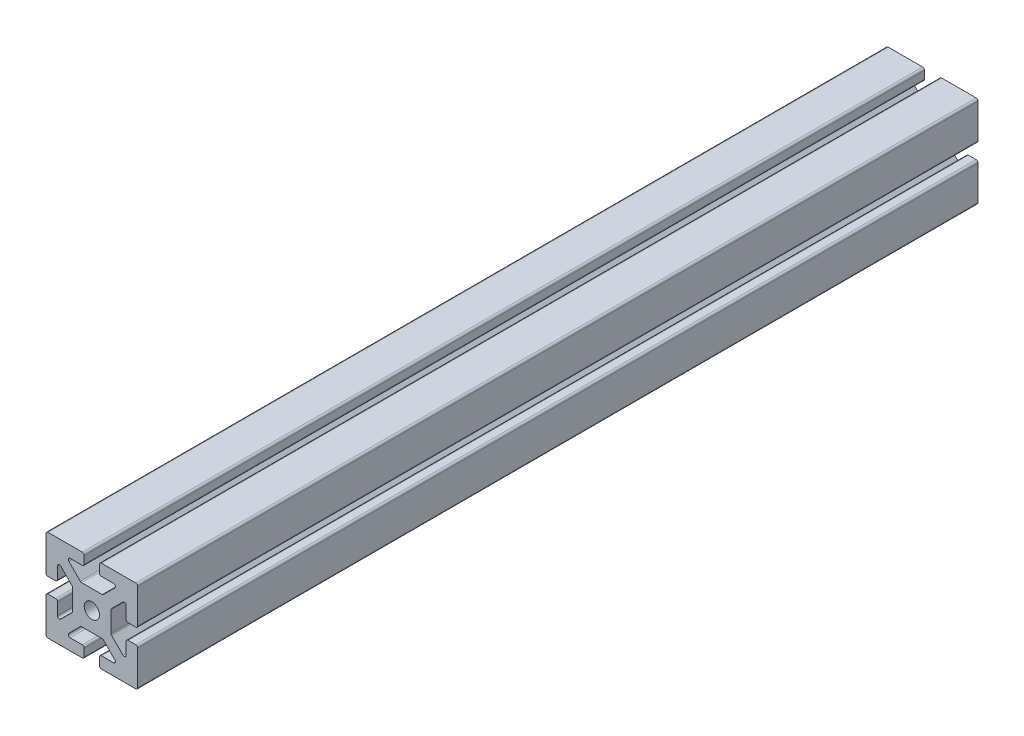
SolidWorks part; units mm, degrees
ref_plane "Front Plane" through (0, 0, 0) normal (0, 0, 1) x (1, 0, 0)
ref_plane "Top Plane" through (0, 0, 0) normal (0, 1, 0) x (1, 0, 0)
ref_plane "Right Plane" through (0, 0, 0) normal (1, 0, 0) x (0, 0, -1)
sketch "Sketch2" plane through (0, 0, 0) normal (0, 0, 1) x (1, 0, 0)
  line L0 (-707.1068, -707.1068) -> (34648.2323, 34648.2323) construction
  line L1 (-2.5, 0) -> (2.5, 0)
  line L2 (0, -2.5) -> (0, 2.5)
  line L3 (0, 2.5) -> (1.3358, 2.5)
  line L4 (2.5, -1.3358) -> (2.5, 1.3358)
  line L5 (1.4393, 2.5) -> (2.5, 1.4393)
  line L6 (1.5126, 2.5732) -> (3.0126, 4.0732)
  line L7 (2.8358, 4.5) -> (1.25, 4.5)
  line L8 (1, 4.75) -> (1, 5.75)
  line L9 (1.25, 6) -> (5.75, 6)
  line L10 (6, 5.75) -> (6, 1.25)
  line L11 (5.75, 1) -> (4.7486, 1)
  line L12 (4.4986, 1.25) -> (4.4986, 2.8344)
  line L13 (4.0718, 3.0111) -> (2.5732, 1.5126)
  line L14 (-707.1068, 707.1068) -> (34648.2323, -34648.2323) construction
  line L15 (4.0718, -3.0111) -> (2.5732, -1.5126)
  line L16 (4.4986, -1.25) -> (4.4986, -2.8344)
  line L17 (5.75, -1) -> (4.7486, -1)
  line L18 (6, -5.75) -> (6, -1.25)
  line L19 (1.25, -6) -> (5.75, -6)
  line L20 (1, -4.75) -> (1, -5.75)
  line L21 (2.8358, -4.5) -> (1.25, -4.5)
  line L22 (1.5126, -2.5732) -> (3.0126, -4.0732)
  line L23 (1.4393, -2.5) -> (2.5, -1.4393)
  line L24 (-1.3358, -2.5) -> (1.3358, -2.5)
  line L25 (707.1068, 707.1068) -> (-34648.2323, -34648.2323) construction
  line L26 (707.1068, -707.1068) -> (-34648.2323, 34648.2323) construction
  line L27 (-1.4393, -2.5) -> (-2.5, -1.4393)
  line L28 (-1.5126, -2.5732) -> (-3.0126, -4.0732)
  line L29 (-2.8358, -4.5) -> (-1.25, -4.5)
  line L30 (-1, -4.75) -> (-1, -5.75)
  line L31 (-1.25, -6) -> (-5.75, -6)
  line L32 (-6, -5.75) -> (-6, -1.25)
  line L33 (-5.75, -1) -> (-4.7486, -1)
  line L34 (-4.4986, -1.25) -> (-4.4986, -2.8344)
  line L35 (-4.0718, -3.0111) -> (-2.5732, -1.5126)
  line L36 (-4.0718, 3.0111) -> (-2.5732, 1.5126)
  line L37 (-4.4986, 1.25) -> (-4.4986, 2.8344)
  line L38 (-5.75, 1) -> (-4.7486, 1)
  line L39 (-6, 5.75) -> (-6, 1.25)
  line L40 (-1.25, 6) -> (-5.75, 6)
  line L41 (-1, 4.75) -> (-1, 5.75)
  line L42 (-2.8358, 4.5) -> (-1.25, 4.5)
  line L43 (-1.5126, 2.5732) -> (-3.0126, 4.0732)
  line L44 (-1.4393, 2.5) -> (-2.5, 1.4393)
  line L45 (-2.5, -1.3358) -> (-2.5, 1.3358)
  line L46 (0, 2.5) -> (-1.3358, 2.5)
  arc A0 (1.3358, 2.5) -> (1.5126, 2.5732) centre (1.3358, 2.75) ccw
  arc A1 (2.5, 1.3358) -> (2.5732, 1.5126) centre (2.75, 1.3358) cw
  arc A2 (3.0126, 4.0732) -> (2.8358, 4.5) centre (2.8358, 4.25) ccw
  arc A3 (4.4986, 2.8344) -> (4.0718, 3.0111) centre (4.2486, 2.8344) ccw
  arc A4 (4.7486, 1) -> (4.4986, 1.25) centre (4.7486, 1.25) cw
  arc A5 (6, 1.25) -> (5.75, 1) centre (5.75, 1.25) cw
  arc A6 (5.75, 6) -> (6, 5.75) centre (5.75, 5.75) cw
  arc A7 (1.25, 4.5) -> (1, 4.75) centre (1.25, 4.75) cw
  arc A8 (1, 5.75) -> (1.25, 6) centre (1.25, 5.75) cw
  arc A9 (1, -5.75) -> (1.25, -6) centre (1.25, -5.75) ccw
  arc A10 (1.25, -4.5) -> (1, -4.75) centre (1.25, -4.75) ccw
  arc A11 (5.75, -6) -> (6, -5.75) centre (5.75, -5.75) ccw
  arc A12 (6, -1.25) -> (5.75, -1) centre (5.75, -1.25) ccw
  arc A13 (4.7486, -1) -> (4.4986, -1.25) centre (4.7486, -1.25) ccw
  arc A14 (4.4986, -2.8344) -> (4.0718, -3.0111) centre (4.2486, -2.8344) cw
  arc A15 (3.0126, -4.0732) -> (2.8358, -4.5) centre (2.8358, -4.25) cw
  arc A16 (2.5, -1.3358) -> (2.5732, -1.5126) centre (2.75, -1.3358) ccw
  arc A17 (1.3358, -2.5) -> (1.5126, -2.5732) centre (1.3358, -2.75) cw
  arc A18 (-1.3358, -2.5) -> (-1.5126, -2.5732) centre (-1.3358, -2.75) ccw
  arc A19 (-2.5, -1.3358) -> (-2.5732, -1.5126) centre (-2.75, -1.3358) cw
  arc A20 (-3.0126, -4.0732) -> (-2.8358, -4.5) centre (-2.8358, -4.25) ccw
  arc A21 (-4.4986, -2.8344) -> (-4.0718, -3.0111) centre (-4.2486, -2.8344) ccw
  arc A22 (-4.7486, -1) -> (-4.4986, -1.25) centre (-4.7486, -1.25) cw
  arc A23 (-6, -1.25) -> (-5.75, -1) centre (-5.75, -1.25) cw
  arc A24 (-5.75, -6) -> (-6, -5.75) centre (-5.75, -5.75) cw
  arc A25 (-1.25, -4.5) -> (-1, -4.75) centre (-1.25, -4.75) cw
  arc A26 (-1, -5.75) -> (-1.25, -6) centre (-1.25, -5.75) cw
  arc A27 (-1, 5.75) -> (-1.25, 6) centre (-1.25, 5.75) ccw
  arc A28 (-1.25, 4.5) -> (-1, 4.75) centre (-1.25, 4.75) ccw
  arc A29 (-5.75, 6) -> (-6, 5.75) centre (-5.75, 5.75) ccw
  arc A30 (-6, 1.25) -> (-5.75, 1) centre (-5.75, 1.25) ccw
  arc A31 (-4.7486, 1) -> (-4.4986, 1.25) centre (-4.7486, 1.25) ccw
  arc A32 (-4.4986, 2.8344) -> (-4.0718, 3.0111) centre (-4.2486, 2.8344) cw
  arc A33 (-3.0126, 4.0732) -> (-2.8358, 4.5) centre (-2.8358, 4.25) cw
  arc A34 (-2.5, 1.3358) -> (-2.5732, 1.5126) centre (-2.75, 1.3358) ccw
  arc A35 (-1.3358, 2.5) -> (-1.5126, 2.5732) centre (-1.3358, 2.75) cw
  circle A36 centre (0, 0) radius 1
  point P0 (-4.4986, -1)
  point P9 (0.6679, 2.5)
  point P28 (4.4986, 1)
  point P31 (6, 1)
  point P34 (6, 6)
  point P37 (1, 4.5)
  point P40 (1, 6)
  point P41 (4.4986, 2.0422)
  point P79 (1, -6)
  point P80 (1, -4.5)
  point P81 (6, -6)
  point P82 (6, -1)
  point P83 (4.4986, -1)
  point P147 (0, 0)
  point P148 (-6, -1)
  point P149 (-6, -6)
  point P150 (-1, -4.5)
  point P151 (-1, -6)
  point P152 (-1, 6)
  point P153 (-1, 4.5)
  point P154 (-6, 6)
  point P155 (-6, 1)
  point P156 (-4.4986, 1)
  dimension "D1" = 0.25
  dimension "D2" = 4.5
  dimension "D10" = 0.75
  dimension "D12" = 2
  dimension "D3" = 1.5
  dimension "D4" = 1.5
  dimension "D5" = 1
  dimension "D6" = 1.5014
  dimension "D7" = 1
  dimension "D8" = 2
  dimension "D9" = 1.9986
  dimension "D11" = 0.75
extrude "Boss-Extrude1" add sketch "Sketch2" against normal blind 110
